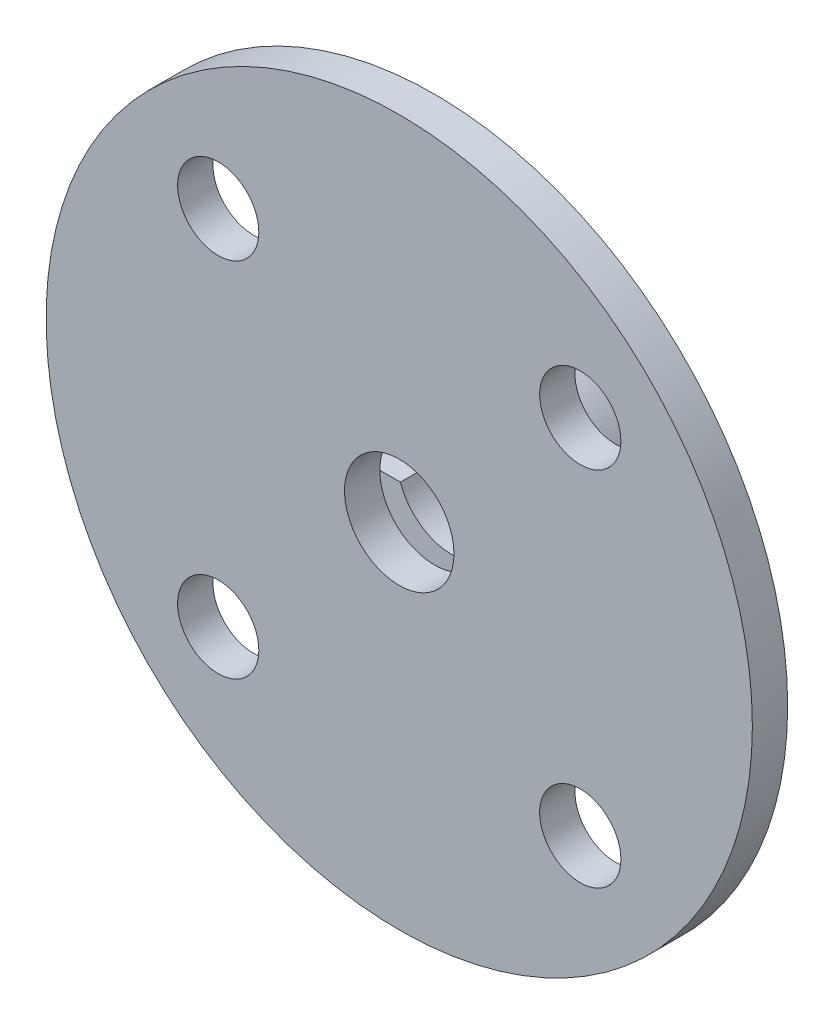
SolidWorks part; units mm, degrees
ref_plane "前视基准面" through (0, 0, 0) normal (0, 0, 1) x (1, 0, 0)
ref_plane "上视基准面" through (0, 0, 0) normal (0, 1, 0) x (1, 0, 0)
ref_plane "右视基准面" through (0, 0, 0) normal (1, 0, 0) x (0, 0, -1)
sketch "草图1" plane through (0, 0, 0) normal (0, 0, 1) x (1, 0, 0)
  circle A1 centre (0, 0) radius 14
  circle A3 centre (-7.0711, 7.0711) radius 1.5
  circle A4 centre (7.0711, 7.0711) radius 1.5
  circle A5 centre (-7.0711, -7.0711) radius 1.5
  circle A6 centre (7.0711, -7.0711) radius 1.5
extrude "凸台-拉伸1" add sketch "草图1" along normal blind 2
sketch "草图2" plane through (0, 0, 0) normal (0, 0, -1) x (-1, 0, 0)
  line L9 (-2.6885, -3.1) -> (2.6885, -3.1)
  line L10 (-2.6833, 3.1) -> (2.6833, 3.1)
  line L14 (-2.6833, -3.1) -> (2.6833, -3.1)
  arc A1 (-2.6833, 3.1) -> (-2.6833, -3.1) centre (0, 0) ccw
  arc A2 (2.6833, 3.1) -> (2.6833, -3.1) centre (0, 0) cw
  point P2 (0, 3.1)
  point P4 (0, -3.1)
extrude "切除-拉伸1" cut sketch "草图2" against normal through all contours A2 L10 A1 L9
sketch "草图3" plane through (0, 0, 0) normal (0, 0, -1) x (-1, 0, 0)
  line L0 (0, 3.1) -> (3.7, 3.1)
  line L1 (-2.6833, 3.1) -> (2.6833, 3.1) construction
  line L2 (3.7, 3.1) -> (3.7, 7.1)
  line L3 (0, 3.1) -> (-3.7, 3.1)
  line L4 (-3.7, 3.1) -> (-3.7, 7.1)
  line L5 (-3.7, 7.1) -> (3.7, 7.1)
extrude "凸台-拉伸4" add sketch "草图3" along normal blind 1
sketch "草图6" plane through (0, 0, -1) normal (0, 0, -1) x (-1, 0, 0)
  circle A2 centre (0, 0) radius 7
  circle A3 centre (0, 0) radius 3.1
extrude "凸台-拉伸5" add sketch "草图6" along normal blind 5
sketch "草图7" plane through (0, 0, -6) normal (0, 0, -1) x (-1, 0, 0)
  line L0 (-2.5, 3.1) -> (-2.5, 6.5383)
  line L2 (-2.5, 3.1) -> (2.5, 3.1)
  line L3 (2.5, 6.5383) -> (2.5, 3.1)
  arc A2 (-2.5, 6.5383) -> (2.5, 6.5383) centre (0, 0) cw
  point P17 (0, 3.1)
extrude "凸台-拉伸6" add sketch "草图7" along normal blind 1
sketch "草图8" plane through (0, 0, -6) normal (0, 0, -1) x (-1, 0, 0)
  line L2 (5.4474, 3) -> (5.4474, 1)
  line L5 (5.4474, 1) -> (13.4474, 1)
  line L6 (13.4474, 1) -> (13.4474, 3)
  line L7 (13.4474, 3) -> (5.4474, 3)
  line L10 (5.4474, -3) -> (13.4474, -3)
  line L11 (13.4474, -3) -> (13.4474, -1)
  line L12 (13.4474, -1) -> (5.4474, -1)
  line L14 (5.4474, -1) -> (5.4474, -3)
extrude "凸台-拉伸7" add sketch "草图8" against normal blind 5
sketch "草图9" plane through (0, 3, 0) normal (0, 1, 0) x (1, 0, 0)
  circle A0 centre (-10.8, 4) radius 1.6
extrude "切除-拉伸3" cut sketch "草图9" against normal through all contours A0
sketch "草图10" plane through (0, 0, -7) normal (0, 0, -1) x (-1, 0, 0)
  line L9 (-2.5, 6.5383) -> (-2.5, 3.1)
  line L10 (2.5, 6.5383) -> (2.5, 3.1)
  arc A2 (-2.5, 3.1) -> (2.5, 3.1) centre (0, 0) ccw
  arc A3 (-2.5, 6.5383) -> (2.5, 6.5383) centre (0, 0) cw
extrude "凸台-拉伸8" add sketch "草图10" along normal blind 2
sketch "草图11" plane through (0, 0, -6) normal (0, 0, -1) x (-1, 0, 0)
  line L0 (13.4474, 1) -> (1.4059, 1)
  line L1 (13.4474, -1) -> (1.4059, -1)
  line L2 (1.4059, -1) -> (1.4059, 1)
  line L3 (13.4474, 1) -> (13.4474, -1)
extrude "切除-拉伸4" cut sketch "草图11" against normal blind 5
sketch "草图12" plane through (0, 0, 2) normal (0, 0, 1) x (1, 0, 0)
  circle A0 centre (0, 0) radius 20
  circle A1 centre (0, 0) radius 3.1
extrude "凸台-拉伸9" add sketch "草图12" against normal blind 2
sketch "草图13" plane through (0, 0, 2) normal (0, 0, 1) x (1, 0, 0)
  line L6 (-10.253, -10.253) -> (10.253, 10.253) construction
  line L7 (-10.253, 10.253) -> (10.253, -10.253) construction
  circle A0 centre (10.253, 10.253) radius 2.3
  circle A1 centre (-10.253, 10.253) radius 2.3
  circle A2 centre (-10.253, -10.253) radius 2.3
  circle A3 centre (10.253, -10.253) radius 2.3
extrude "切除-拉伸5" cut sketch "草图13" against normal blind 2
sketch "草图14" plane through (0, 0, -1) normal (0, 0, -1) x (-1, 0, 0)
  line L0 (-4.5909, 5.2843) -> (-4.5909, 9.7386)
  line L1 (-4.5909, 9.7386) -> (4.7248, 9.7386)
  line L2 (4.7248, 9.7386) -> (4.7248, 5.1649)
  arc A0 (-4.5909, 5.2843) -> (4.7248, 5.1649) centre (0, 0) cw
  arc A1 (-2.5, 6.5383) -> (6.3246, -3) centre (0, 0) ccw construction
extrude "切除-拉伸6" cut sketch "草图14" against normal blind 1
fillet "圆角1" radius 3 1 edges at (0, 7, -9)
fillet "圆角2" radius 1.5 4 edges at (-13.4474, -2, -1) (-13.4474, -2, -6) (-13.4474, 2, -1) (-13.4474, 2, -6)
